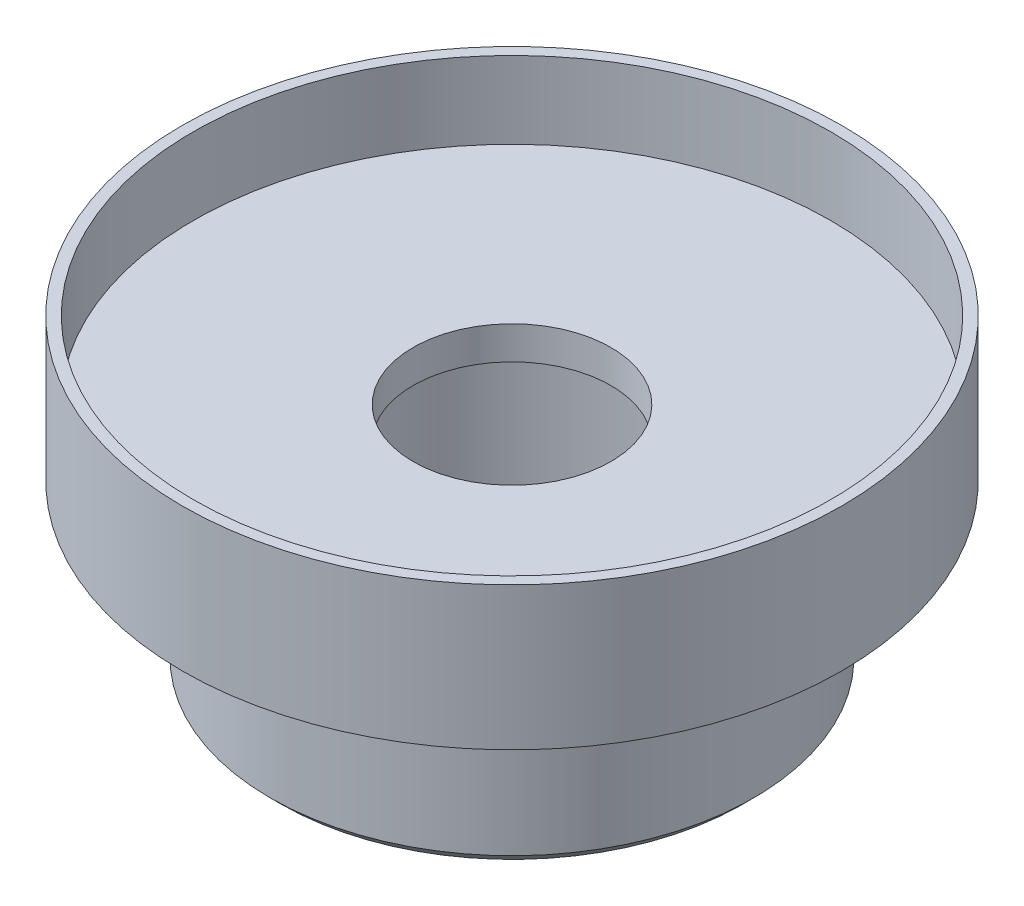
SolidWorks part; units mm, degrees
ref_plane "Plan de face" through (0, 0, 0) normal (0, 0, 1) x (1, 0, 0)
ref_plane "Plan de dessus" through (0, 0, 0) normal (0, 1, 0) x (1, 0, 0)
ref_plane "Plan de droite" through (0, 0, 0) normal (1, 0, 0) x (0, 0, -1)
sketch "Esquisse1" plane through (0, 0, 0) normal (0, 1, 0) x (1, 0, 0)
  circle A0 centre (0, 0) radius 11
  dimension "D1" = 22
extrude "Boss.-Extru.1" add sketch "Esquisse1" along normal blind 7.5
sketch "Esquisse3" plane through (0, 7.5, 0) normal (0, 1, 0) x (1, 0, 0)
  circle A0 centre (0, 0) radius 15
  dimension "D1" = 30
extrude "Boss.-Extru.2" add sketch "Esquisse3" along normal blind 6.5
chamfer "Chanfrein1" distance 0.5 angle 45 1 edges at (0, 0, 11)
chamfer "Chanfrein2" distance 1 angle 45 1 edges at (0, 7.5, 11)
sketch "Esquisse4" plane through (0, 14, 0) normal (0, 1, 0) x (1, 0, 0)
  circle A0 centre (0, 0) radius 14.5
  dimension "D1" = 29
extrude "Enlèv. mat.-Extru.1" cut sketch "Esquisse4" against normal blind 3.5
sketch "Esquisse5" plane through (0, 10.5, 0) normal (0, 1, 0) x (1, 0, 0)
  circle A0 centre (0, 0) radius 4.5
  dimension "D1" = 9
extrude "Enlèv. mat.-Extru.2" cut sketch "Esquisse5" against normal blind 1.5 contours A0
sketch "Esquisse6" plane through (0, 9, 0) normal (0, 1, 0) x (1, 0, 0)
  circle A0 centre (0, 0) radius 7
  dimension "D1" = 14
extrude "Enlèv. mat.-Extru.3" cut sketch "Esquisse6" against normal blind 1
sketch "Esquisse8" plane through (0, 8, 0) normal (0, 1, 0) x (1, 0, 0)
  circle A0 centre (0, 0) radius 8
  dimension "D1" = 16
extrude "Enlèv. mat.-Extru.4" cut sketch "Esquisse8" against normal through all
